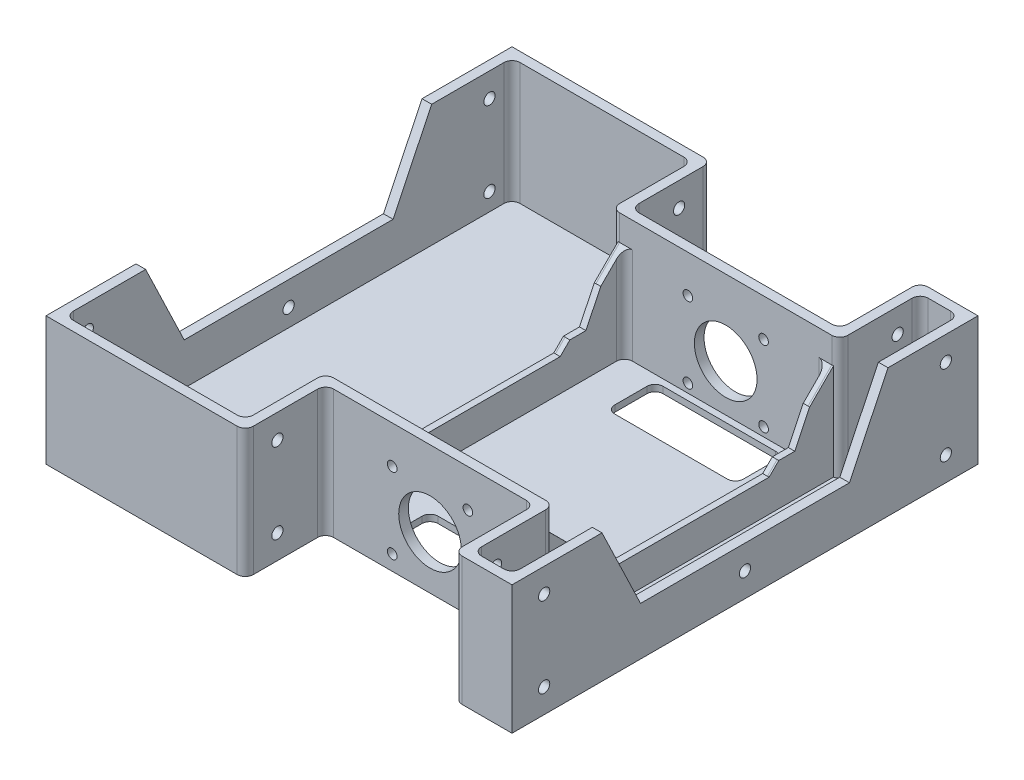
SolidWorks part; units mm, degrees
ref_plane "Спереди" through (0, 0, 0) normal (0, 0, 1) x (1, 0, 0)
ref_plane "Сверху" through (0, 0, 0) normal (0, 1, 0) x (1, 0, 0)
ref_plane "Справа" through (0, 0, 0) normal (1, 0, 0) x (0, 0, -1)
sketch "Эскиз1" plane through (0, 0, 0) normal (0, 1, 0) x (1, 0, 0)
  line L1 (-145, -145) -> (145, -145)
  line L2 (-145, -145) -> (-145, 145)
  line L3 (-145, 145) -> (145, 145)
  line L4 (145, -145) -> (145, 145)
  line L5 (0, 145) -> (0, -145) construction
  line L6 (-145, 0) -> (145, 0) construction
  point P0 (0, 0)
  dimension "D1" = 290
  dimension "D2" = 290
extrude "Бобышка-Вытянуть1" add sketch "Эскиз1" along normal blind 4
sketch "Эскиз2" plane through (0, 4, 0) normal (0, 1, 0) x (1, 0, 0)
  line L0 (0, 157.2547) -> (0, 0) construction
  line L1 (145, 145) -> (109, 145)
  line L2 (145, 145) -> (145, 0.2395)
  line L5 (0, 0) -> (241.6766, 0) construction
  line L8 (145, -145) -> (145, 0.2395)
  line L11 (139, 139) -> (139, -139)
  line L13 (145, 145) -> (-145, 145) construction
  line L14 (109, 145) -> (109, 95)
  line L15 (109, 95) -> (-21, 95)
  line L16 (-21, 95) -> (-21, 145)
  line L17 (-21, 145) -> (-139, 145)
  line L18 (-139, 145) -> (-139, 139)
  line L19 (-139, 139) -> (-27, 139)
  line L20 (-27, 139) -> (-27, 89)
  line L21 (-27, 89) -> (115, 89)
  line L22 (115, 89) -> (115, 139)
  line L23 (115, 139) -> (139, 139)
  line L24 (-145, 145) -> (-145, -145) construction
  line L25 (115, -139) -> (139, -139)
  line L26 (115, -89) -> (115, -139)
  line L27 (-27, -89) -> (115, -89)
  line L28 (-27, -139) -> (-27, -89)
  line L29 (-139, -139) -> (-27, -139)
  line L30 (-139, -145) -> (-139, -139)
  line L31 (-21, -145) -> (-139, -145)
  line L32 (-21, -95) -> (-21, -145)
  line L33 (109, -95) -> (-21, -95)
  line L34 (109, -145) -> (109, -95)
  line L35 (145, -145) -> (109, -145)
  point P14 (139, 0)
  dimension "D1" = 6
  dimension "D2" = 6
  dimension "D3" = 6
  dimension "D4" = 50
  dimension "D5" = 6
  dimension "D6" = 6
  dimension "60" = 36
  dimension "D7" = 6
  dimension "D8" = 130
  dimension "D9" = 6
extrude "Бобышка-Вытянуть2" add sketch "Эскиз2" along normal blind 76
sketch "Эскиз16" plane through (0, 4, 0) normal (0, 1, 0) x (1, 0, 0)
  line L0 (0, 0) -> (227.8261, 0) construction
  line L1 (-21, 145) -> (109, 145)
  line L2 (-21, 145) -> (-21, 95)
  line L3 (-21, 95) -> (109, 95)
  line L4 (109, 145) -> (109, 95)
  line L5 (-21, -95) -> (109, -95)
  line L6 (109, -145) -> (109, -95)
  line L7 (-21, -145) -> (109, -145)
  line L8 (-21, -145) -> (-21, -95)
extrude "Вырез-Вытянуть11" cut sketch "Эскиз16" against normal blind 10
sketch "Эскиз4" plane through (0, 4, 0) normal (0, 1, 0) x (1, 0, 0)
  line L0 (-145, -145) -> (-139, -145) construction
  line L1 (-145, 145) -> (-139, 145)
  line L2 (-145, 145) -> (-145, -145)
  line L3 (-145, -145) -> (-139, -145)
  line L4 (-139, 145) -> (-139, -145)
  dimension "D1" = 6
extrude "Бобышка-Вытянуть3" add sketch "Эскиз4" along normal up to surface (76 mm away) up to face at (29.8333, 80, 0)
sketch "Эскиз7" plane through (0, 4, 0) normal (0, 1, 0) x (1, 0, 0)
  line L0 (0, 158.6534) -> (0, 0) construction
  line L1 (0, 0) -> (246.672, 0) construction
  line L2 (145, -145) -> (145, 145) construction
  line L8 (47, 0) -> (147, 0) construction
  line L11 (-38, -75) -> (126, -75) construction
  line L12 (-38, -75) -> (-38, 75) construction
  line L13 (-38, 75) -> (126, 75) construction
  line L14 (126, -75) -> (126, 75) construction
  line L15 (44, 75) -> (44, -75) construction
  line L16 (-38, 0) -> (126, 0) construction
  line L18 (-31, -82) -> (119, -82) construction
  line L19 (-31, -82) -> (-31, 82) construction
  line L20 (-31, 82) -> (119, 82) construction
  line L21 (119, -82) -> (119, 82) construction
  line L22 (44, 82) -> (44, -82) construction
  line L23 (-31, 0) -> (119, 0) construction
  circle A16 centre (119, 82) radius 2
  circle A17 centre (126, 75) radius 2
  circle A18 centre (-31, 82) radius 2
  circle A19 centre (-38, 75) radius 2
  circle A20 centre (119, -82) radius 2
  circle A22 centre (126, -75) radius 2
  circle A23 centre (-38, -75) radius 2
  circle A24 centre (-31, -82) radius 2
  point P44 (44, 0)
  point P50 (44, 0)
  dimension "D12" = 4
  dimension "D2" = 101
  dimension "D7" = 164
  dimension "D8" = 150
  dimension "D10" = 164
  dimension "D11" = 150
extrude "Вырез-Вытянуть3" cut sketch "Эскиз7" against normal blind 10
sketch "Эскиз14" plane through (0, 4, 0) normal (0, 1, 0) x (1, 0, 0)
  line L0 (44, 159.053) -> (44, -165.8467) construction
  line L1 (145, -145) -> (145, 145) construction
  line L3 (4, 55) -> (84, 55)
  line L4 (4, 55) -> (4, 85)
  line L5 (4, 85) -> (84, 85)
  line L6 (84, 55) -> (84, 85)
  line L7 (44, 85) -> (44, 55) construction
  line L8 (4, 70) -> (84, 70) construction
  line L9 (0, 0) -> (180.733, 0) construction
  line L10 (4, -85) -> (84, -85)
  line L11 (84, -55) -> (84, -85)
  line L12 (4, -55) -> (84, -55)
  line L13 (4, -55) -> (4, -85)
  line L14 (-27, 89) -> (115, 89) construction
  point P4 (44, 70)
  dimension "D1" = 101
  dimension "D2" = 80
  dimension "D3" = 30
  dimension "D4" = 4
extrude "Вырез-Вытянуть9" cut sketch "Эскиз14" against normal blind 20
sketch "Эскиз15" plane through (-145, 0, 0) normal (-1, 0, 0) x (0, 0, 1)
  line L0 (0, 107.7828) -> (0, 40) construction
  line L1 (0, 40) -> (185.6693, 40) construction
  line L2 (-145, 0) -> (145, 0) construction
  line L3 (-171.7731, 65) -> (170.5378, 65) construction
  circle A0 centre (0, 65) radius 3.5
  circle A1 centre (125, 65) radius 3.5
  circle A2 centre (-125, 65) radius 3.5
  circle A3 centre (-125, 15) radius 3.5
  circle A4 centre (125, 15) radius 3.5
  circle A5 centre (0, 15) radius 3.5
  dimension "D3" = 7
  dimension "D4" = 125
  dimension "D1" = 40
  dimension "D2" = 25
extrude "Вырез-Вытянуть10" cut sketch "Эскиз15" against normal through all both and the other way through all
fillet "Скругление1" radius 5 20 edges at (109, 40, -145) (109, 40, -95) (-21, 40, -95) (-21, 40, -145) (-139, 42, -139) (-27, 42, -139) (-27, 42, -89) (115, 42, -89) (115, 42, -139) (139, 42, -139) (139, 42, 139) (115, 42, 139) (115, 42, 89) (-27, 42, 89) (-27, 42, 139) (-139, 42, 139) (-21, 40, 145) (-21, 40, 95) (109, 40, 95) (109, 40, 145)
sketch "Эскиз17" plane through (0, 0, 95) normal (0, 0, 1) x (1, 0, 0)
  line L0 (44, 114.7773) -> (44, 33) construction
  line L1 (44, 33) -> (168.181, 33) construction
  line L2 (145, 80) -> (145, 0) construction
  line L4 (110, 4) -> (-22, 4) construction
  line L6 (20.45, 9.45) -> (67.55, 9.45) construction
  line L7 (20.45, 9.45) -> (20.45, 56.55) construction
  line L8 (20.45, 56.55) -> (67.55, 56.55) construction
  line L9 (67.55, 9.45) -> (67.55, 56.55) construction
  line L10 (44, 56.55) -> (44, 9.45) construction
  line L11 (20.45, 33) -> (67.55, 33) construction
  circle A0 centre (44, 33) radius 19.5
  circle A1 centre (20.45, 56.55) radius 3
  circle A2 centre (20.45, 56.55) radius 3
  circle A3 centre (20.45, 56.55) radius 3
  circle A4 centre (67.55, 56.55) radius 3
  circle A5 centre (67.55, 9.45) radius 3
  circle A6 centre (20.45, 9.45) radius 3
  dimension "D3" = 39
  dimension "D5" = 6
  dimension "D1" = 101
  dimension "D2" = 29
  dimension "D4" = 47.1
extrude "Вырез-Вытянуть12" cut sketch "Эскиз17" against normal through all both and the other way through all contours A0 | A1 | A4 | A5 | A6
sketch "Эскиз18" plane through (0, 4, 0) normal (0, 1, 0) x (1, 0, 0)
  line L0 (-195.7624, 0) -> (208.5106, 0) construction
  line L1 (-21, 118.2107) -> (-21, -110.4846) construction
  line L2 (-21, 100) -> (-21, 140) construction
  line L3 (104, 95) -> (-16, 95) construction
  line L4 (109, -100) -> (109, -140) construction
  line L5 (109, -110.4846) -> (109, 120) construction
  line L6 (109, 140) -> (109, 100) construction
  line L7 (-23, -95) -> (-19, -95)
  line L8 (-23, -95) -> (-23, 95)
  line L9 (-23, 95) -> (-19, 95)
  line L10 (-19, -95) -> (-19, 95)
  line L11 (-21, 95) -> (-21, -95) construction
  line L12 (-23, 0) -> (-19, 0) construction
  line L14 (111, -95) -> (107, -95)
  line L15 (111, -95) -> (111, 95)
  line L16 (111, 95) -> (107, 95)
  line L17 (107, -95) -> (107, 95)
  line L18 (109, 95) -> (109, -95) construction
  line L19 (111, 0) -> (107, 0) construction
  point P16 (-21, 0)
  point P20 (109, 0)
  dimension "D1" = 4
  dimension "D2" = 4
extrude "Бобышка-Вытянуть4" add sketch "Эскиз18" along normal blind 20
chamfer "Фаска1" distance 40 angle 45 8 edges at (110.5025, 24, 89.0253) (108.5, 24, 89) (-22.5025, 24, 89.0253) (-20.5, 24, 89) (-22.5025, 24, -89.0253) (-20.5, 24, -89) (110.5025, 24, -89.0253) (108.5, 24, -89)
sketch "Эскиз19" plane through (145, 0, 0) normal (1, 0, 0) x (0, 0, -1)
  line L0 (0, 117.0161) -> (0, 30) construction
  line L1 (0, 30) -> (182.1669, 30) construction
  line L2 (-145, 0) -> (145, 0) construction
  line L3 (-65, 30) -> (65, 30)
  line L4 (65, 30) -> (89, 80)
  line L5 (-145, 80) -> (145, 80) construction
  line L6 (89, 80) -> (-89, 80)
  line L7 (145, 80) -> (145, 0) construction
  line L8 (-65, 30) -> (-89, 80)
  point P14 (0, 80)
  dimension "D1" = 30
  dimension "D2" = 56
  dimension "D3" = 130
extrude "Вырез-Вытянуть13" cut sketch "Эскиз19" against normal through all both and the other way through all
fillet "Скругление2" radius 5 12 edges at (107, 34, 89) (-19, 34, 89) (107, 34, -89) (84, 2, 85) (84, 2, 55) (4, 2, 55) (4, 2, 85) (4, 2, -85) (4, 2, -55) (84, 2, -55) (84, 2, -85) (-19, 34, -89)
